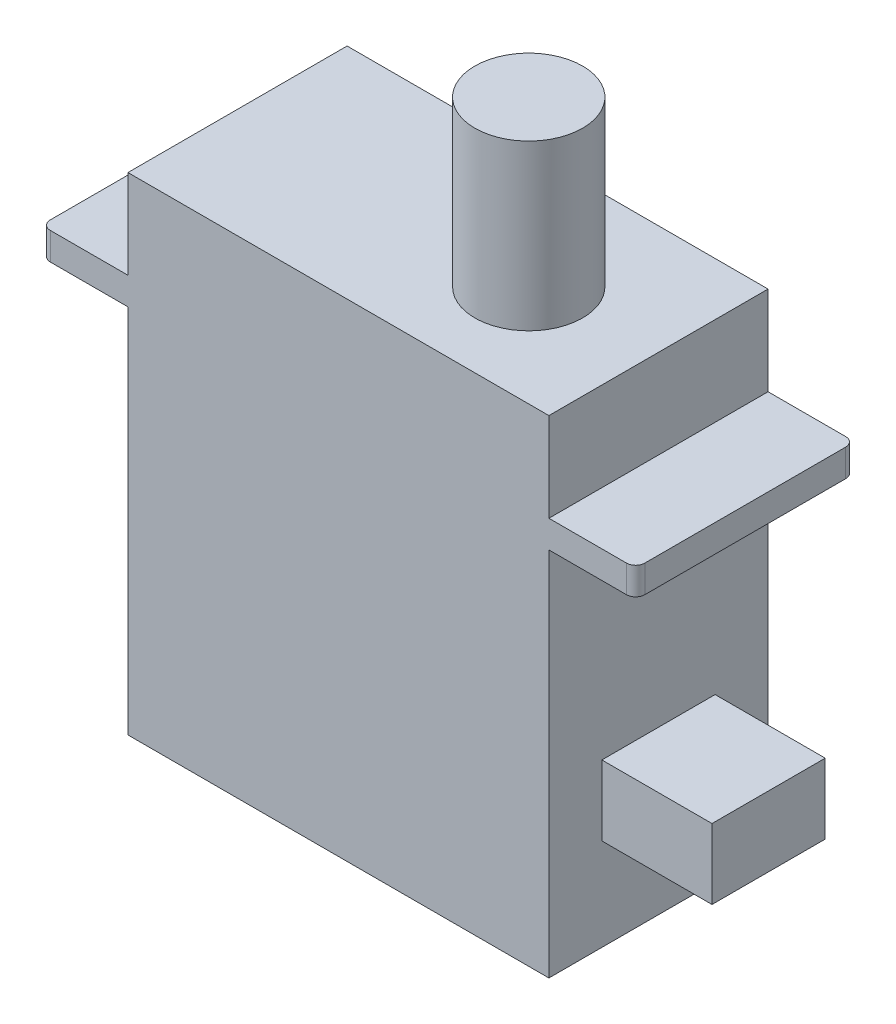
SolidWorks part; units mm, degrees
material "ABS"
ref_plane "Front Plane" through (0, 0, 0) normal (0, 0, 1) x (1, 0, 0)
ref_plane "Top Plane" through (0, 0, 0) normal (0, 1, 0) x (1, 0, 0)
ref_plane "Right Plane" through (0, 0, 0) normal (1, 0, 0) x (0, 0, -1)
sketch "Sketch1" plane through (0, 0, 0) normal (0, 0, 1) x (1, 0, 0)
  line L1 (0, 0) -> (23.05, 0)
  line L2 (0, 0) -> (0, 26.67)
  line L3 (0, 26.67) -> (23.05, 26.67)
  line L4 (23.05, 0) -> (23.05, 26.67)
  dimension "D1" = 23.05
  dimension "D2" = 26.67
extrude "Boss-Extrude1" add sketch "Sketch1" along normal blind 12
sketch "Sketch2" plane through (23.05, 0, 0) normal (1, 0, 0) x (0, 0, -1)
  line L0 (-12, 0) -> (-12, 26.67) construction
  line L1 (-12, 21.8) -> (0, 21.8)
  line L2 (-12, 21.8) -> (-12, 20.3)
  line L3 (-12, 20.3) -> (0, 20.3)
  line L4 (0, 21.8) -> (0, 20.3)
  line L5 (0, 0) -> (0, 26.67) construction
  line L6 (-12, 0) -> (0, 0) construction
  dimension "D1" = 21.8
  dimension "D2" = 1.5
extrude "Boss-Extrude2" add sketch "Sketch2" along normal blind 4.75
fillet "Fillet1" radius 0.5 2 edges at (27.8, 21.05, 0) (27.8, 21.05, 12)
sketch "Sketch3" plane through (0, 0, 0) normal (-1, 0, 0) x (0, 0, 1)
  line L0 (0, 26.67) -> (0, 0) construction
  line L1 (0, 21.8) -> (12, 21.8)
  line L2 (0, 21.8) -> (0, 20.3)
  line L3 (0, 20.3) -> (12, 20.3)
  line L4 (12, 21.8) -> (12, 20.3)
  line L5 (12, 26.67) -> (12, 0) construction
  line L6 (12, 0) -> (0, 0) construction
  dimension "D1" = 1.5
  dimension "D2" = 21.8
extrude "Boss-Extrude3" add sketch "Sketch3" along normal blind 4.75
fillet "Fillet2" radius 0.5 2 edges at (-4.75, 21.05, 0) (-4.75, 21.05, 12)
sketch "Sketch4" plane through (23.05, 0, 0) normal (1, 0, 0) x (0, 0, -1)
  line L0 (-0.5, 21.8) -> (-11.5, 21.8) construction
  line L1 (-9.1, 8.89) -> (-2.9, 8.89)
  line L2 (-9.1, 8.89) -> (-9.1, 5.05)
  line L3 (-9.1, 5.05) -> (-2.9, 5.05)
  line L4 (-2.9, 8.89) -> (-2.9, 5.05)
  line L5 (0, 0) -> (0, 20.3) construction
  line L6 (-12, 0) -> (-12, 20.3) construction
  dimension "D1" = 16.75
  dimension "D2" = 2.9
  dimension "D3" = 2.9
  dimension "D4" = 3.84
extrude "Boss-Extrude4" add sketch "Sketch4" along normal blind 6.03
sketch "Sketch5" plane through (0, 26.67, 0) normal (0, 1, 0) x (1, 0, 0)
  circle A0 centre (16.3956, -6.4497) radius 2.95
  dimension "D1" = 5.9
extrude "Boss-Extrude5" add sketch "Sketch5" along normal blind 9
sketch "Sketch6" [suppressed] plane through (0, 35.67, 0) normal (0, 1, 0) x (1, 0, 0)
  circle A0 centre (16.3956, -6.4497) radius 17.33
  dimension "D1" = 34.66
extrude "Boss-Extrude6" [suppressed] add sketch "Sketch6" against normal blind 4.9
sketch "Sketch7" [suppressed] plane through (0, 35.67, 0) normal (0, 1, 0) x (1, 0, 0)
  line L2 (16.3956, -6.4497) -> (33.7256, -6.4497) construction
  line L3 (19.1645, -13.4047) -> (14.3025, -8.5428)
  line L4 (19.1645, 0.5053) -> (14.3025, -4.3567)
  circle A0 centre (16.3956, -6.4497) radius 17.33 construction
  arc A1 (33.6261, -4.5959) -> (33.6261, -8.3036) centre (16.3956, -6.4497) ccw
  arc A2 (19.1645, -13.4047) -> (33.6261, -8.3036) centre (25.1749, -7.3943) ccw
  arc A3 (19.1645, 0.5053) -> (33.6261, -4.5959) centre (25.1749, -5.5051) cw
  arc A4 (14.3025, -4.3567) -> (14.3025, -8.5428) centre (16.3956, -6.4497) ccw
  dimension "D1" = 8.5
extrude "Cut-Extrude1" [suppressed] cut sketch "Sketch7" against normal blind 4.9 contours A1 A2 L3 A4 L4 A3
